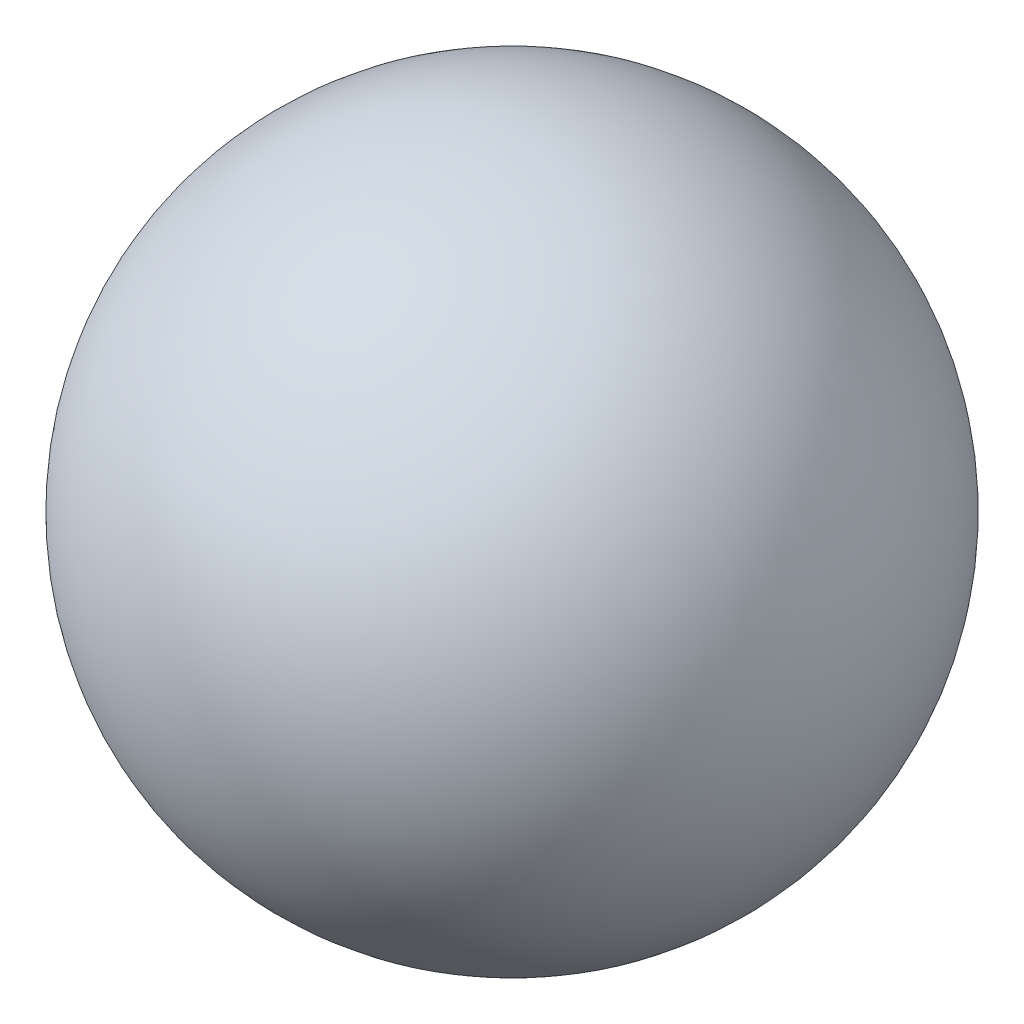
SolidWorks part; units mm, degrees
material "201 Acier inoxydable recuit (SS)"
ref_plane "Plan de face" through (0, 0, 0) normal (0, 0, 1) x (1, 0, 0)
ref_plane "Plan de dessus" through (0, 0, 0) normal (0, 1, 0) x (1, 0, 0)
ref_plane "Plan de droite" through (0, 0, 0) normal (1, 0, 0) x (0, 0, -1)
sketch "Esquisse1" plane through (0, 0, 0) normal (0, 0, 1) x (1, 0, 0)
  line L0 (0, 11.6606) -> (0, -11.3198) construction
  line L1 (0, 9) -> (0, -9)
  arc A0 (0, 9) -> (0, -9) centre (0, 0) ccw
  dimension "D1" = 9
revolve "Révolution2" add sketch "Esquisse1" angle 360 about L0
